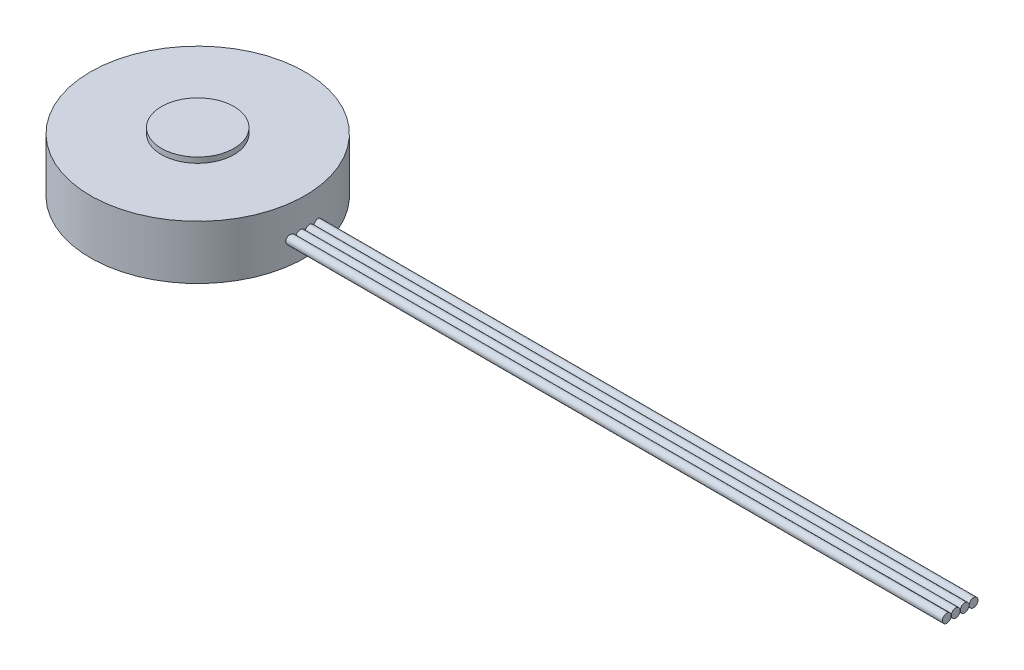
SolidWorks part; units mm, degrees
material "ABS"
ref_plane "Front Plane" through (0, 0, 0) normal (0, 0, 1) x (1, 0, 0)
ref_plane "Top Plane" through (0, 0, 0) normal (0, 1, 0) x (1, 0, 0)
ref_plane "Right Plane" through (0, 0, 0) normal (1, 0, 0) x (0, 0, -1)
sketch "Sketch2" plane through (0, 0, 0) normal (0, 0, 1) x (1, 0, 0)
  line L0 (0, 0) -> (-9.85, 0)
  line L1 (-9.85, 0) -> (-9.85, 4.95)
  line L2 (-9.85, 4.95) -> (-3.329, 4.95)
  line L3 (-3.329, 4.95) -> (-3.329, 5.45)
  line L4 (-3.329, 5.45) -> (0, 5.45)
  line L5 (0, 5.45) -> (0, 0)
  dimension "D1" = 9.85
  dimension "D2" = 4.95
  dimension "D3" = 5.45
revolve "Revolve1" add sketch "Sketch2" angle 360 about L5
sketch "Sketch3" plane through (0, 0, 0) normal (1, 0, 0) x (0, 0, -1)
  line L1 (9.85, 4.95) -> (-9.85, 4.95) construction
  line L2 (0, 0) -> (0, 4.95) construction
  circle A0 centre (-0.41, 2.05) radius 0.405
  circle A4 centre (-1.23, 2.05) radius 0.405
  circle A5 centre (1.23, 2.05) radius 0.405
  circle A6 centre (0.41, 2.05) radius 0.405
  dimension "D1" = 0.81
  dimension "D4" = 0.41
  dimension "D2" = 2.9
  dimension "D3" = 2
extrude "Boss-Extrude2" add sketch "Sketch3" along normal blind 70
equation "\"D1@Sketch2\"=19.7/2"
